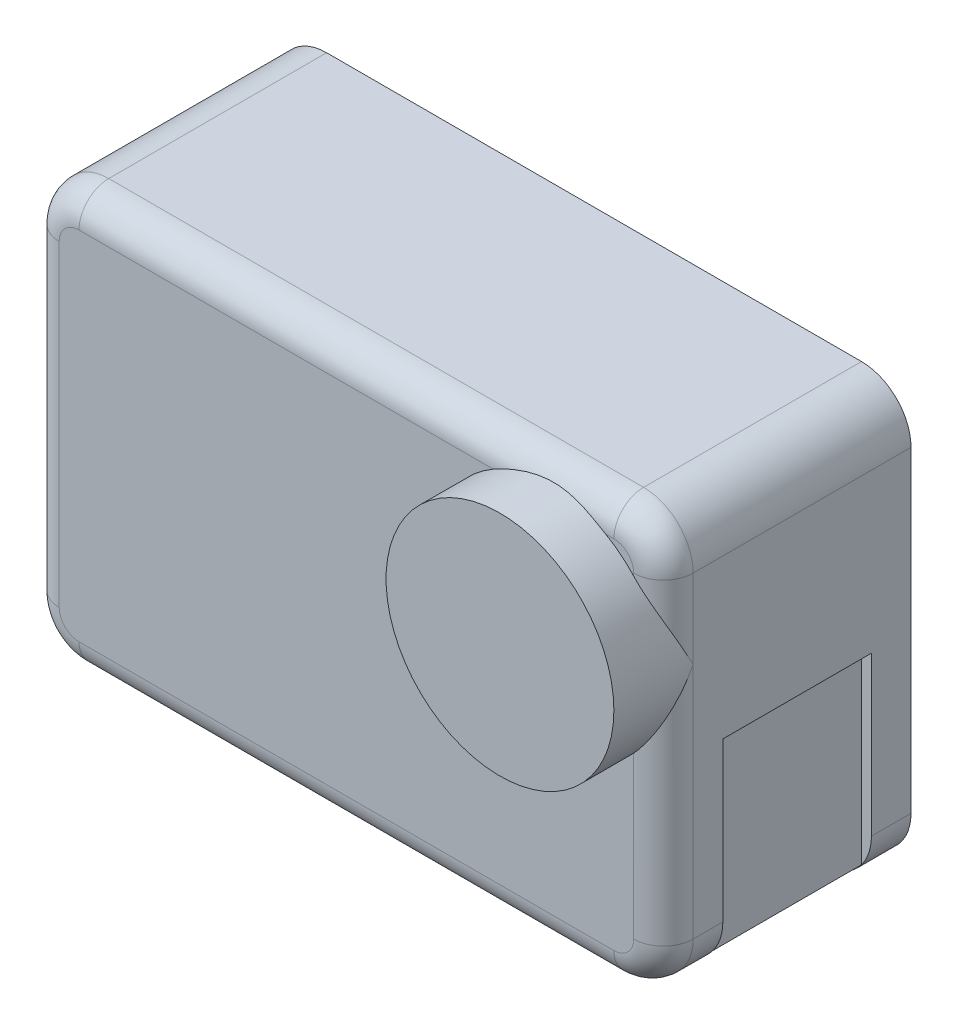
SolidWorks part; units mm, degrees
ref_plane "Front Plane" through (0, 0, 0) normal (0, 0, 1) x (1, 0, 0)
ref_plane "Top Plane" through (0, 0, 0) normal (0, 1, 0) x (1, 0, 0)
ref_plane "Right Plane" through (0, 0, 0) normal (1, 0, 0) x (0, 0, -1)
sketch "Sketch1" plane through (0, 0, 0) normal (0, 0, 1) x (1, 0, 0)
  line L1 (0, 0) -> (64, 0)
  line L2 (0, 0) -> (0, 42)
  line L3 (0, 42) -> (64, 42)
  line L4 (64, 0) -> (64, 42)
  dimension "D1" = 64
  dimension "D2" = 42
extrude "Boss-Extrude1" add sketch "Sketch1" along normal blind 25
sketch "Sketch2" plane through (0, 0, 25) normal (0, 0, 1) x (1, 0, 0)
  line L1 (64, 0) -> (64, 42) construction
  line L2 (64, 42) -> (0, 42) construction
  circle A0 centre (52.5, 29) radius 11.5
  dimension "D1" = 23
  dimension "D2" = 13
fillet "Fillet2" radius 5 4 edges at (64, 0, 12.5) (0, 0, 12.5) (0, 42, 12.5) (64, 42, 12.5)
fillet "Fillet4" radius 3 8 edges at (64, 21, 25) (62.5355, 40.5355, 25) (62.5355, 1.4645, 25) (32, 0, 25) (1.4645, 1.4645, 25) (0, 21, 25) (1.4645, 40.5355, 25) (32, 42, 25)
extrude "Boss-Extrude3" add sketch "Sketch2" along normal blind 5 and the other way up to next contours A0
sketch "Sketch3" plane through (64, 0, 0) normal (1, 0, 0) x (0, 0, -1)
  line L0 (0, 0) -> (-22, 0) construction
  line L1 (-19, 21) -> (-4, 21)
  line L2 (-19, 21) -> (-19, 0)
  line L3 (-19, 0) -> (-4, 0)
  line L4 (-4, 21) -> (-4, 0)
  line L5 (0, 5) -> (0, 37) construction
  dimension "D1" = 15
  dimension "D2" = 21
  dimension "D3" = 4
extrude "Cut-Extrude1" cut sketch "Sketch3" against normal blind 1
sketch "Sketch4" plane through (63, 0, 0) normal (1, 0, 0) x (0, 0, -1)
  line L0 (0, 0) -> (-22, 0) construction
  line L1 (-4, 0) -> (-19, 0)
  line L2 (-4, 0) -> (-4, 2)
  line L3 (-4, 2) -> (-19, 2)
  line L4 (-19, 0) -> (-19, 2)
  dimension "D1" = 4
extrude "Cut-Extrude2" cut sketch "Sketch4" against normal blind 5
